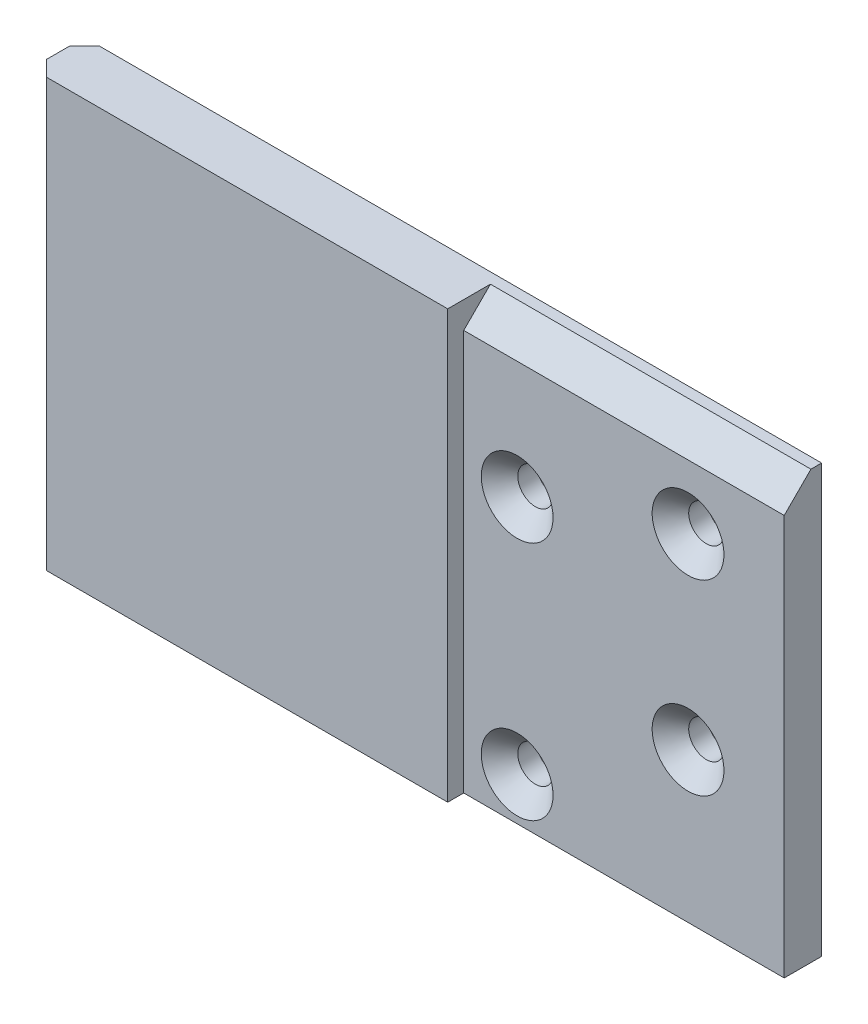
SolidWorks part; units mm, degrees
material "AISI 1045 Aço, trefilado"
ref_plane "Plano frontal" through (0, 0, 0) normal (0, 0, 1) x (1, 0, 0)
ref_plane "Plano superior" through (0, 0, 0) normal (0, 1, 0) x (1, 0, 0)
ref_plane "Plano direito" through (0, 0, 0) normal (1, 0, 0) x (0, 0, -1)
sketch "Esboço1" plane through (0, 0, 0) normal (0, 1, 0) x (1, 0, 0)
  line L0 (0, 0) -> (0, 7)
  line L1 (0, 7) -> (-135.2252, 7)
  line L2 (-138, -0.1356) -> (-135.1356, -3)
  line L3 (-135.1356, -3) -> (-60, -3)
  line L4 (-60, -3) -> (-60, 0)
  line L5 (-60, 0) -> (0, 0)
  line L6 (-138, -0.1356) -> (-138, 4.2252)
  line L7 (-138, 4.2252) -> (-135.2252, 7)
  point P2 (-138.0484, 7)
  point P8 (-138.0484, 7)
  point P11 (-140.9128, 4.2252)
  dimension "D1" = 138
  dimension "D2" = 45
  dimension "D3" = 10
  dimension "D4" = 7
  dimension "D5" = 45
  dimension "D6" = 60
extrude "Ressalto-extrusão1" add sketch "Esboço1" along normal blind 80
chamfer "Chanfro2" distance 5 angle 45 1 edges at (-30, 80, 0)
hole_wizard "Escareado para parafuso Allen sextavado escareado de M62" positions "Esboço3" profile "Esboço4" countersink size "M6" standard "ISO" end condition through all
sketch "Esboço3" plane through (0, 0, 0) normal (0, 0, 1) x (1, 0, 0)
  line L0 (-60, 80) -> (0, 80) construction
  line L1 (-60, 0) -> (0, 0) construction
  line L2 (0, 75) -> (0, 0) construction
  point P0 (-18, 63)
  point P2 (-50, 53)
  point P4 (-18, 28)
  point P6 (-50, 8)
  dimension "D1" = 17
  dimension "D2" = 27
  dimension "D3" = 8
  dimension "D4" = 28
  dimension "D5" = 18
  dimension "D6" = 18
  dimension "D7" = 32
  dimension "D8" = 32
sketch "Esboço4" plane through (-18, 63, 0) normal (1, 0, 0) x (0, -1, 0)
  line L0 (0, 0) -> (0, 7)
  line L1 (0, 7) -> (3.3, 7)
  line L2 (3.3, 7) -> (3.3, 3.42)
  line L3 (3.3, 3.42) -> (6.72, 0)
  line L5 (6.72, 0) -> (0, 0)
  line L6 (-3.3, 3.42) -> (-6.72, 0) construction
  line L11 (0, -6.35) -> (0, 107.95) construction
  dimension "Thru Hole Dia." = 6.6
  dimension "Thru Hole Depth" = 7
  dimension "Near C'Sink Dia." = 13.44
  dimension "Near C'Sink Angle" = 90
